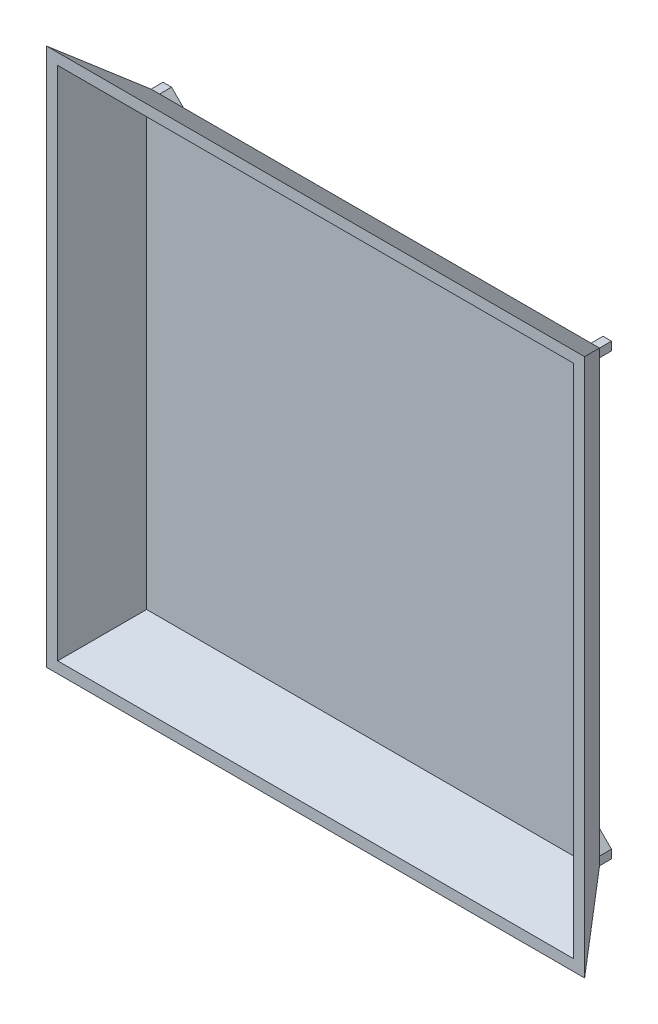
SolidWorks part; units mm, degrees
ref_plane "前视基准面" through (0, 0, 0) normal (0, 0, 1) x (1, 0, 0)
ref_plane "上视基准面" through (0, 0, 0) normal (0, 1, 0) x (1, 0, 0)
ref_plane "右视基准面" through (0, 0, 0) normal (1, 0, 0) x (0, 0, -1)
other "Configuration Table"
sketch "草图1" plane through (0, 0, 0) normal (0, 0, 1) x (1, 0, 0)
  line L1 (0, 0) -> (150, 0)
  line L2 (0, 0) -> (0, -150)
  line L3 (0, -150) -> (150, -150)
  line L4 (150, 0) -> (150, -150)
  dimension "D1" = 150
  dimension "D2" = 150
ref_plane "基准面1" through (0, 0, 0) normal (0, 0, 1) x (1, 0, 0)
ref_plane "基准面2" through (0, 0, 20) normal (0, 0, 1) x (1, 0, 0)
sketch "草图3" plane through (0, 0, 20) normal (0, 0, 1) x (1, 0, 0)
  line L7 (-15, 15) -> (165, 15)
  line L8 (-15, 15) -> (-15, -165)
  line L9 (-15, -165) -> (165, -165)
  line L10 (165, 15) -> (165, -165)
  point P12 (75, -75)
  dimension "D1" = 180
  dimension "D2" = 180
loft "放样1" add profiles "草图3", "草图1"
shell "抽壳2" thickness 3
sketch "草图4" plane through (0, 0, 3) normal (0, 0, 1) x (1, 0, 0)
  line L0 (75, -1.5) -> (75, -165)
  line L1 (148.5, -1.5) -> (1.5, -1.5) construction
  line L2 (-15, -165) -> (165, -165) construction
  line L3 (-15, -75) -> (165, -75)
  line L4 (-15, 15) -> (-15, -165) construction
  line L5 (165, -165) -> (165, 15) construction
  circle A0 centre (66.25, -75) radius 7 construction
  circle A1 centre (66.25, -75) radius 4
  circle A2 centre (66.25, -68) radius 1.5
  circle A3 centre (66.25, -82) radius 1.5
  circle A4 centre (73.25, -75) radius 1.5
  circle A5 centre (59.25, -75) radius 1.5
  circle A6 centre (84.75, -75) radius 1.5
  circle A7 centre (47.75, -75) radius 1.5
  dimension "D1" = 8
  dimension "D2" = 14
  dimension "D3" = 3
  dimension "D4" = 3
  dimension "D5" = 3
  dimension "D6" = 3
  dimension "D7" = 3
  dimension "D8" = 3
  dimension "D9" = 37
  dimension "D10" = 18.5
extrude "切除-拉伸1" cut sketch "草图4" against normal blind 10 contours L3 A6 | L3 A6 | A3 | L3 A4 | L3 A4 | A2 | L3 A5 | L3 A5 | L3 A7 | L3 A7
sketch "草图6" plane through (0, 0, 3) normal (0, 0, 1) x (1, 0, 0)
  line L2 (38.15, -62.5) -> (34.15, -62.5)
  line L5 (38.15, -75) -> (38.15, -62.5)
  line L6 (38.15, -75) -> (38.15, -87.5)
  line L7 (94.35, -75) -> (94.35, -62.5)
  line L8 (94.35, -75) -> (94.35, -87.5)
  line L9 (94.35, -62.5) -> (98.35, -62.5)
  line L11 (98.35, -87.5) -> (94.35, -87.5)
  line L12 (98.35, -87.5) -> (101.35, -87.5)
  line L13 (101.35, -87.5) -> (101.35, -84.5)
  line L14 (98.35, -62.5) -> (101.35, -62.5)
  line L15 (101.35, -62.5) -> (101.35, -65.5)
  line L16 (38.15, -87.5) -> (34.15, -87.5)
  line L17 (34.15, -62.5) -> (31.15, -62.5)
  line L18 (31.15, -62.5) -> (31.15, -65.5)
  line L19 (34.15, -87.5) -> (31.15, -87.5)
  line L20 (31.15, -87.5) -> (31.15, -84.5)
  line L21 (31.15, -65.5) -> (34.15, -65.5)
  line L22 (31.15, -84.5) -> (34.15, -84.5)
  line L23 (34.15, -84.5) -> (34.15, -65.5)
  line L24 (101.35, -65.5) -> (98.35, -65.5)
  line L25 (101.35, -84.5) -> (98.35, -84.5)
  line L26 (98.35, -84.5) -> (98.35, -65.5)
extrude "凸台-拉伸1" add sketch "草图6" against normal blind 40.5
sketch "草图7" plane through (98.35, 0, 0) normal (1, 0, 0) x (0, 0, -1)
  line L0 (0, -65.5) -> (0, -84.5)
  line L1 (0, -75) -> (16.5, -75)
  line L2 (16.5, -75) -> (33.5, -75)
  line L3 (33.5, -75) -> (37.5, -75)
  line L4 (37.5, -84.5) -> (37.5, -65.5) construction
  circle A0 centre (16.5, -75) radius 1.51
  circle A1 centre (33.5, -75) radius 1.51
extrude "切除-拉伸2" cut sketch "草图7" against normal blind 100 contours L2 A0 L1 | L1 A0 L2 | L3 A1 L2 | L2 A1 L3
sketch "草图8" plane through (0, 0, 3) normal (0, 0, 1) x (1, 0, 0)
  circle A0 centre (66.25, -68) radius 1.5
  circle A1 centre (59.25, -75) radius 1.5
  circle A2 centre (47.75, -75) radius 1.5
  circle A3 centre (73.25, -75) radius 1.5
  circle A4 centre (84.75, -75) radius 1.5
  circle A5 centre (66.25, -82) radius 1.5
extrude "凸台-拉伸2" add sketch "草图8" against normal blind 3 contours A0
sketch "草图9" plane through (0, 0, 0) normal (0, 0, -1) x (-1, 0, 0)
  line L3 (-73.5858, -76.4142) -> (0, -2.8284)
  line L4 (0, 0) -> (0, -150) construction
  line L5 (0, -2.8284) -> (0, 0)
  line L6 (-72.7486, -69.9202) -> (-2.8284, 0)
  line L7 (-150, 0) -> (0, 0) construction
  line L8 (-2.8284, 0) -> (0, 0)
  line L9 (-72.7486, -69.9202) -> (-150, -147.1716)
  line L10 (-150, -150) -> (-150, 0) construction
  line L11 (-150, -147.1716) -> (-150, -150)
  line L12 (-73.5858, -76.4142) -> (-147.1716, -150)
  line L14 (0, -150) -> (-150, -150) construction
  line L15 (-147.1716, -150) -> (-150, -150)
extrude "凸台-拉伸3" add sketch "草图9" along normal blind 4 contours L9 L11 L15 L12 L3 L5 L8 L6
sketch "草图10" plane through (0, 0, 0) normal (0, 0, -1) x (-1, 0, 0)
  line L3 (-106.6693, -40.5023) -> (-147.1716, 0)
  line L4 (-150, 0) -> (-2.8284, 0) construction
  line L5 (-147.1716, 0) -> (-150, 0)
  line L6 (-121.9738, -30.8546) -> (-150, -2.8284)
  line L7 (-150, -147.1716) -> (-150, 0) construction
  line L8 (-150, -2.8284) -> (-150, 0)
  line L9 (-106.6693, -40.5023) -> (0, -147.1716)
  line L10 (0, -2.8284) -> (0, -150) construction
  line L11 (0, -147.1716) -> (0, -150)
  line L12 (-121.9738, -30.8546) -> (-2.8284, -150)
  line L13 (0, -150) -> (-147.1716, -150) construction
  line L14 (-2.8284, -150) -> (0, -150)
extrude "凸台-拉伸4" add sketch "草图10" along normal blind 4 contours L3 L5 L8 L6 L12 L14 L11 L9
sketch "草图11" plane through (0, 0, -4) normal (0, 0, -1) x (-1, 0, 0)
  line L1 (-94.35, -62.5) -> (-38.15, -62.5)
  line L2 (-94.35, -62.5) -> (-94.35, -87.5)
  line L3 (-94.35, -87.5) -> (-38.15, -87.5)
  line L4 (-38.15, -62.5) -> (-38.15, -87.5)
extrude "切除-拉伸3" cut sketch "草图11" against normal blind 4 contours L2 L1 L4 L3
